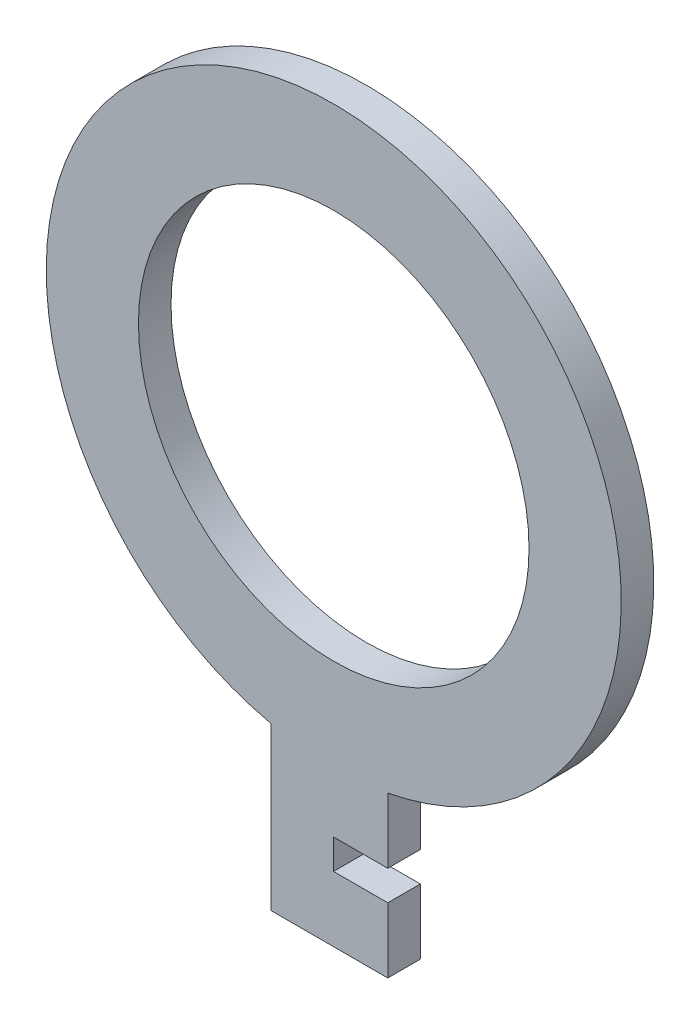
SolidWorks part; units mm, degrees
ref_plane "Alzado" through (0, 0, 0) normal (0, 0, 1) x (1, 0, 0)
ref_plane "Planta" through (0, 0, 0) normal (0, 1, 0) x (1, 0, 0)
ref_plane "Vista lateral" through (0, 0, 0) normal (1, 0, 0) x (0, 0, -1)
sketch "Croquis1" plane through (0, 0, 0) normal (0, 0, 1) x (1, 0, 0)
  line L0 (94, 227.5) -> (470, 227.5) construction
  line L1 (69.9384, 17.6712) -> (59.1984, 17.6712)
  line L2 (64.962, 31.9444) -> (64.962, 84.908) construction
  line L3 (69.9384, 17.6712) -> (69.9384, 23.6712)
  line L4 (59.1984, 17.6712) -> (59.1984, 32.5843)
  line L5 (69.9384, 26.4212) -> (64.9384, 26.4212)
  line L7 (64.9384, 26.4212) -> (64.9384, 23.6712)
  line L8 (69.9384, 23.6712) -> (64.9384, 23.6712)
  line L9 (69.9384, 26.4212) -> (69.9384, 32.4212)
  arc A0 (69.9384, 32.4212) -> (59.1984, 32.5843) centre (64.962, 58.4262) ccw
  circle A1 centre (64.962, 58.4262) radius 17.986
  dimension "D1" = 35.9719
  dimension "D2" = 26.4769
  dimension "D3" = 10.74
  dimension "D4" = 6
  dimension "D5" = 6
  dimension "D6" = 2.75
  dimension "D7" = 5
extrude "Saliente-Extruir1" add sketch "Croquis1" along normal blind 3
